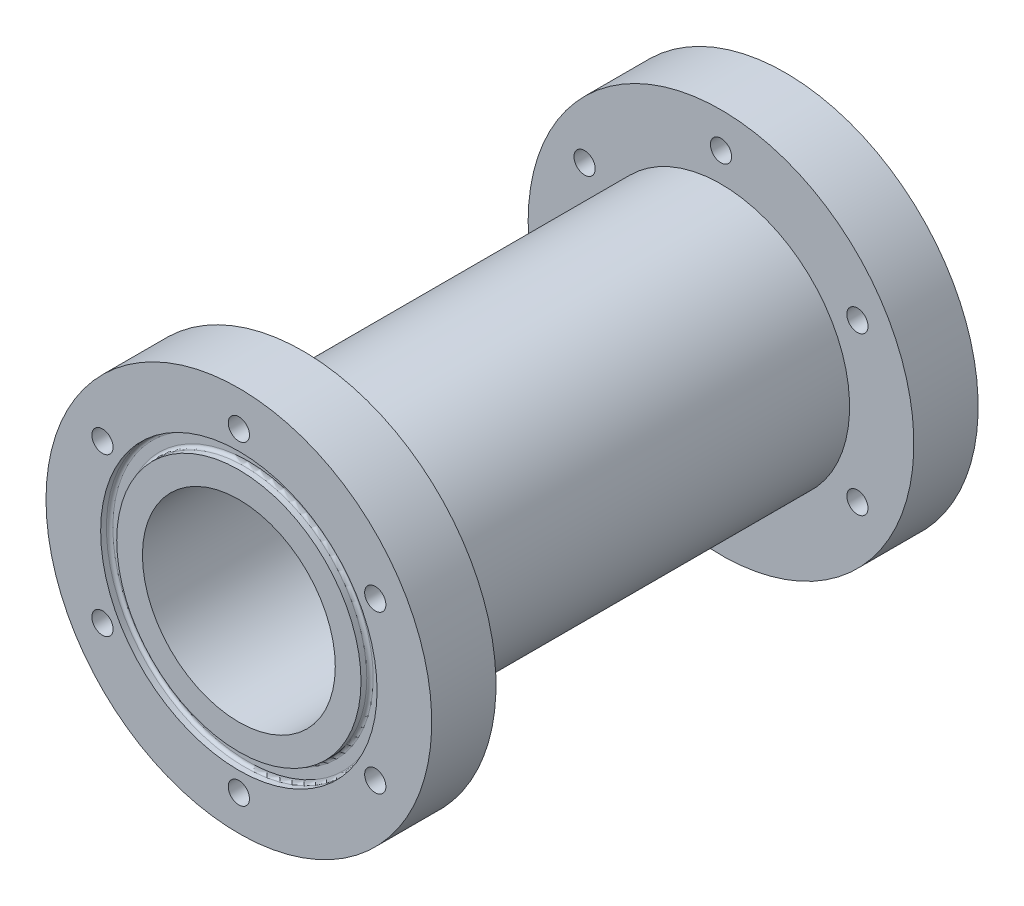
SolidWorks part; units mm, degrees
ref_plane "Front Plane" through (0, 0, 0) normal (0, 0, 1) x (1, 0, 0)
ref_plane "Top Plane" through (0, 0, 0) normal (0, 1, 0) x (1, 0, 0)
ref_plane "Right Plane" through (0, 0, 0) normal (1, 0, 0) x (0, 0, -1)
sketch "Sketch1" plane through (0, 0, 0) normal (0, 0, 1) x (1, 0, 0)
  circle A0 centre (0, 0) radius 15
  circle A1 centre (0, 0) radius 20
  dimension "D1" = 30
  dimension "D2" = 40
extrude "Boss-Extrude1" add sketch "Sketch1" along normal mid plane 85
sketch "Sketch2" plane through (0, 0, -42.5) normal (0, 0, -1) x (-1, 0, 0)
  circle A0 centre (0, 0) radius 30
  circle A1 centre (0, 0) radius 20 construction
  circle A2 centre (0, 0) radius 20
  dimension "D1" = 60
extrude "Boss-Extrude2" add sketch "Sketch2" against normal blind 10
hole_wizard "M4 Tapped Hole1" positions "Sketch3" profile "Sketch4" tap size "M4" standard "ISO" end condition up to next
sketch "Sketch3" plane through (0, 0, -42.5) normal (0, 0, -1) x (-1, 0, 0)
  point P0 (0, 24.5)
  dimension "D1" = 24.5
sketch "Sketch4" plane through (0, 24.5, -42.5) normal (1, 0, 0) x (0, 1, 0)
  line L0 (0, 0) -> (0, 10)
  line L1 (0, 10) -> (1.65, 10)
  line L2 (1.65, 10) -> (1.65, 0)
  line L5 (1.65, 0) -> (0, 0)
  line L11 (0, -6.35) -> (0, 107.95) construction
  dimension "Thru Tap Drill Dia." = 3.3
  dimension "Thru Tap Drill Depth" = 10
cosmetic thread "Hole Thread1" parameters "D2"=4
pattern_circular "CirPattern1" count 6 over 360 about axis through (0, 0, 0) along (0, 0, 1) of "M4 Tapped Hole1"
cosmetic thread "Hole Thread2"
cosmetic thread "Hole Thread3"
cosmetic thread "Hole Thread4"
cosmetic thread "Hole Thread5"
cosmetic thread "Hole Thread6"
sketch "Sketch5" plane through (0, 0, -42.5) normal (0, 0, -1) x (-1, 0, 0)
  circle A0 centre (0, 0) radius 19
  circle A1 centre (0, 0) radius 21.5
  dimension "D1" = 43
  dimension "D2" = 2.5
extrude "Cut-Extrude1" cut sketch "Sketch5" against normal blind 1.4
fillet "Fillet1" radius 0.5 2 edges at (-19, 0, -41.1) (-21.5, 0, -41.1)
mirror "Mirror1" about plane through (0, 0, 0) normal (0, 0, 1) of "Fillet1", "Cut-Extrude1", "CirPattern1", "M4 Tapped Hole1", "Boss-Extrude2"
cosmetic thread "Hole Thread7"
cosmetic thread "Hole Thread8"
cosmetic thread "Hole Thread9"
cosmetic thread "Hole Thread10"
cosmetic thread "Hole Thread11"
cosmetic thread "Hole Thread12"
